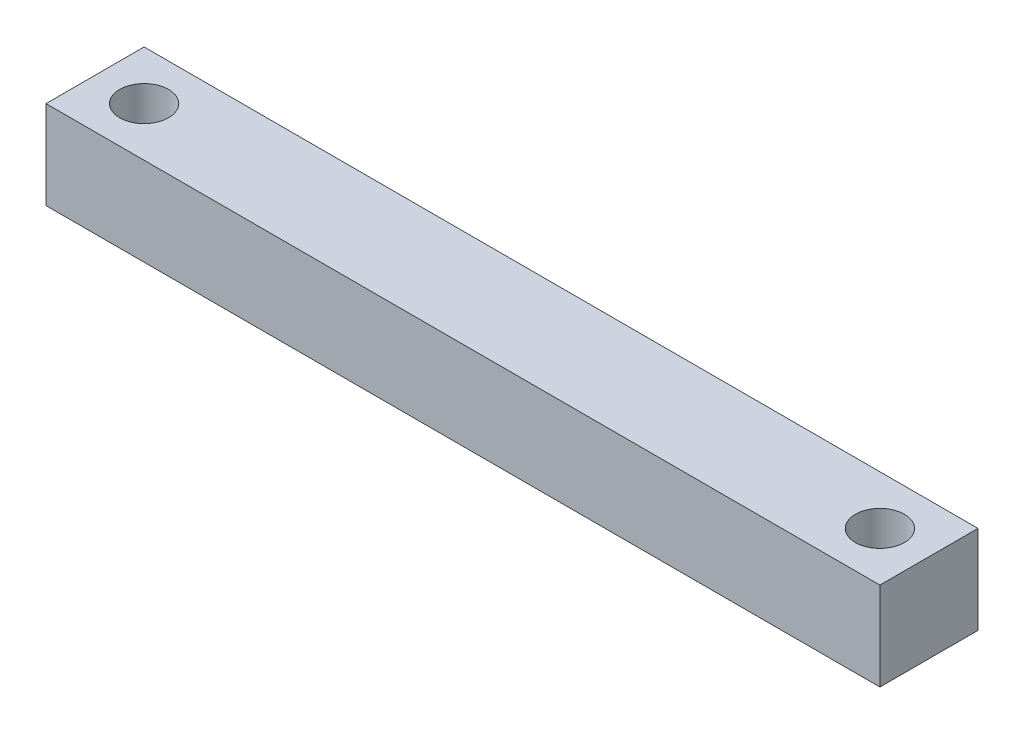
SolidWorks part; units mm, degrees
ref_plane "Front Plane" through (0, 0, 0) normal (0, 0, 1) x (1, 0, 0)
ref_plane "Top Plane" through (0, 0, 0) normal (0, 1, 0) x (1, 0, 0)
ref_plane "Right Plane" through (0, 0, 0) normal (1, 0, 0) x (0, 0, -1)
sketch "Sketch1" plane through (0, 0, 0) normal (0, 1, 0) x (1, 0, 0)
  line L1 (-42.5, 5) -> (42.5, 5)
  line L2 (-42.5, 5) -> (-42.5, -5)
  line L3 (-42.5, -5) -> (42.5, -5)
  line L4 (42.5, 5) -> (42.5, -5)
  point P4 (0, -5)
  point P6 (-42.5, 0)
  dimension "D1" = 85
  dimension "D2" = 10
extrude "Boss-Extrude1" add sketch "Sketch1" along normal blind 9.0049
sketch "Sketch2" plane through (0, 9.0049, 0) normal (0, 1, 0) x (1, 0, 0)
  line L0 (-37.5, 2.5) -> (-37.5, 5) construction
  line L1 (42.5, 5) -> (-42.5, 5) construction
  line L2 (-37.5, -2.5) -> (-37.5, -5) construction
  line L3 (-42.5, -5) -> (42.5, -5) construction
  line L4 (-40, 0) -> (-42.5, 0) construction
  line L5 (-42.5, 5) -> (-42.5, -5) construction
  line L6 (37.5, 2.5) -> (37.5, 5) construction
  line L7 (40, 0) -> (42.5, 0) construction
  line L8 (42.5, -5) -> (42.5, 5) construction
  line L9 (37.5, -2.5) -> (37.5, -5) construction
  circle A0 centre (-37.5, 0) radius 2.5
  circle A1 centre (37.5, 0) radius 2.5
  dimension "D1" = 5
extrude "Cut-Extrude1" cut sketch "Sketch2" against normal through all
